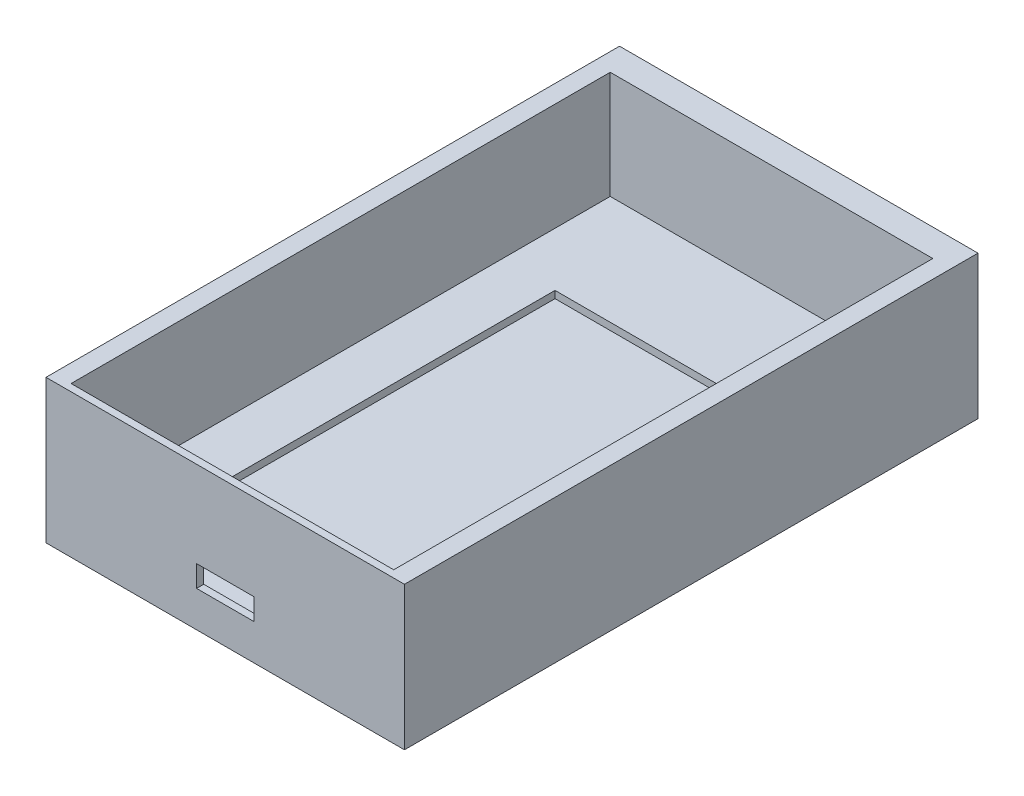
SolidWorks part; units mm, degrees
ref_plane "Front Plane" through (0, 0, 0) normal (0, 0, 1) x (1, 0, 0)
ref_plane "Top Plane" through (0, 0, 0) normal (0, 1, 0) x (1, 0, 0)
ref_plane "Right Plane" through (0, 0, 0) normal (1, 0, 0) x (0, 0, -1)
sketch "Sketch1" plane through (0, 0, 0) normal (0, 0, 1) x (1, 0, 0)
  line L1 (25, -10) -> (-25, -10)
  line L2 (25, -10) -> (25, 10)
  line L3 (25, 10) -> (-25, 10)
  line L4 (-25, -10) -> (-25, 10)
  line L5 (25, -10) -> (-25, 10) construction
  line L6 (25, 10) -> (-25, -10) construction
  point P0 (0, 0)
  dimension "D1" = 50
  dimension "D2" = 20
extrude "Boss-Extrude1" add sketch "Sketch1" along normal mid plane 80
sketch "Sketch2" plane through (0, 10, 0) normal (0, 1, 0) x (1, 0, 0)
  line L0 (0, 10.228) -> (0, -42.5004) construction
  line L1 (22.5, -39) -> (-22.5, -39)
  line L2 (22.5, -39) -> (22.5, 36.2)
  line L3 (22.5, 36.2) -> (-22.5, 36.2)
  line L4 (-22.5, -39) -> (-22.5, 36.2)
  line L5 (22.5, -39) -> (-22.5, 36.2) construction
  line L6 (22.5, 36.2) -> (-22.5, -39) construction
  line L7 (25, -40) -> (-25, -40) construction
  line L8 (25, 40) -> (-25, 40) construction
  point P0 (0, -1.4)
  dimension "D1" = 3.8
  dimension "D2" = 45
  dimension "D3" = 1
extrude "Cut-Extrude1" cut sketch "Sketch2" against normal blind 15
sketch "Sketch3" plane through (0, 0, 40) normal (0, 0, 1) x (1, 0, 0)
  line L0 (25, 10) -> (-25, 10) construction
  line L1 (4, -5) -> (-4, -5)
  line L2 (4, -5) -> (4, -2)
  line L3 (4, -2) -> (-4, -2)
  line L4 (-4, -5) -> (-4, -2)
  line L5 (4, -5) -> (-4, -2) construction
  line L6 (4, -2) -> (-4, -5) construction
  line L7 (0, 6.1966) -> (0, -19.3916) construction
  point P0 (0, -3.5)
  dimension "D1" = 8
  dimension "D2" = 3
  dimension "D3" = 15
extrude "Cut-Extrude2" cut sketch "Sketch3" against normal up to next
sketch "Sketch4" plane through (0, -5, 0) normal (0, 1, 0) x (1, 0, 0)
  line L1 (15, -39) -> (-15, -39)
  line L2 (15, -39) -> (15, 21)
  line L3 (15, 21) -> (-15, 21)
  line L4 (-15, -39) -> (-15, 21)
  line L5 (15, -39) -> (-15, 21) construction
  line L6 (15, 21) -> (-15, -39) construction
  line L7 (0, 12.9452) -> (0, -52.3512) construction
  line L8 (-22.5, -39) -> (22.5, -39) construction
  point P0 (0, -44.3505)
  point P7 (0, -9)
  dimension "D1" = 60
  dimension "D2" = 30
extrude "Cut-Extrude3" cut sketch "Sketch4" against normal blind 1
